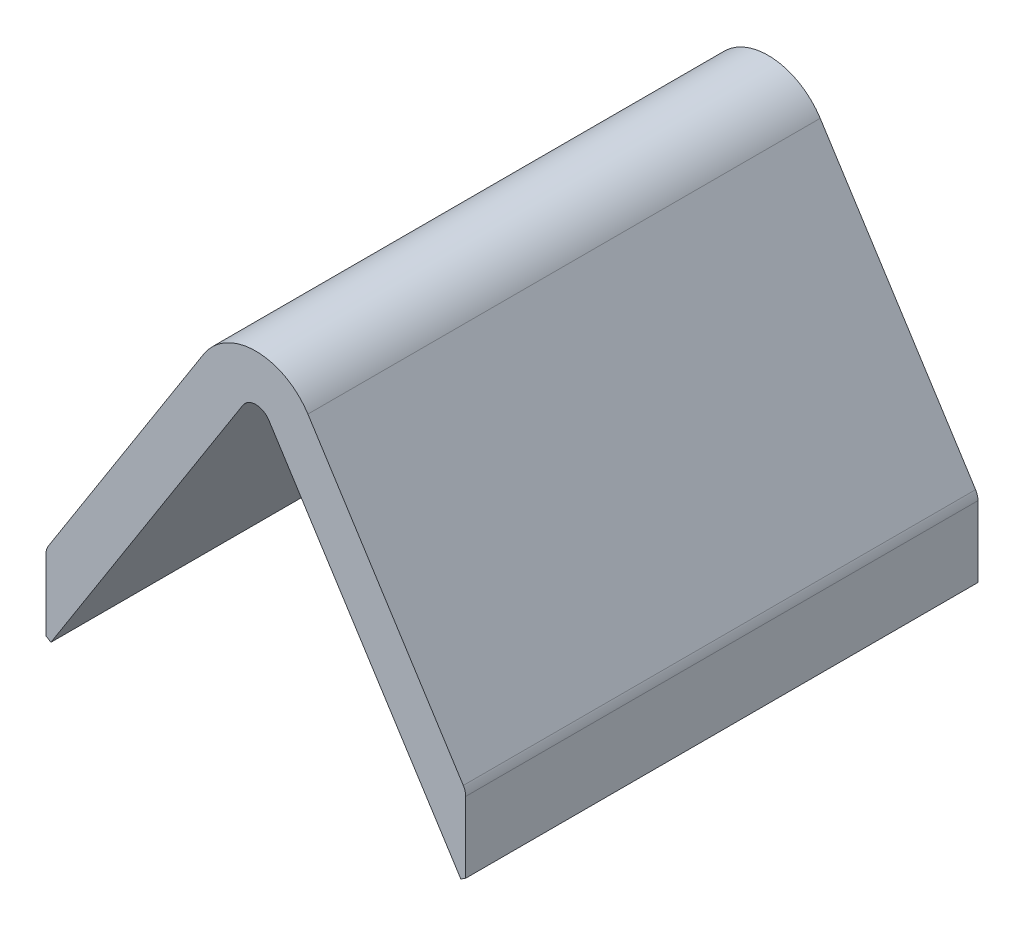
SolidWorks part; units mm, degrees
material "Custom Plastic"
ref_plane "Front Plane" through (0, 0, 0) normal (0, 0, 1) x (1, 0, 0)
ref_plane "Top Plane" through (0, 0, 0) normal (0, 1, 0) x (1, 0, 0)
ref_plane "Right Plane" through (0, 0, 0) normal (1, 0, 0) x (0, 0, -1)
sketch "Sketch1" plane through (0, 0, 0) normal (0, 0, 1) x (1, 0, 0)
  line L0 (0, 0) -> (0, 145.7232) construction
  line L1 (-70.5, -139) -> (70.5, -139) construction
  line L2 (-70.5, -139) -> (-70.5, 139) construction
  line L3 (-70.5, 139) -> (70.5, 139) construction
  line L4 (70.5, -139) -> (70.5, 139) construction
  line L5 (-70.5, -139) -> (70.5, 139) construction
  line L6 (-70.5, 139) -> (70.5, -139) construction
  line L7 (0, 145.7232) -> (-68, 38.9846) construction
  line L8 (-65.5, 9.4079) -> (-1.6868, 109.5746)
  line L9 (-68.0302, 11.0198) -> (-4.217, 111.1865)
  line L10 (-65.5, 9.4079) -> (-68.0302, 11.0198)
  line L11 (-65.5, 9.4079) -> (-65.5, 8.4079)
  line L12 (-65.5, 8.4079) -> (-70.5, 8.4079)
  line L13 (-70.5, 8.4079) -> (-70.5, 37.3253)
  line L14 (-67.217, 40.2137) -> (-16.8678, 119.246)
  line L15 (-68, 14.5577) -> (-68, 37.5272)
  line L16 (-18.5546, 120.3206) -> (-69.717, 40.0118)
  line L17 (65.5, 9.4079) -> (65.5, 8.4079)
  line L18 (65.5, 9.4079) -> (68.0302, 11.0198)
  line L19 (65.5, 8.4079) -> (70.5, 8.4079)
  line L20 (70.5, 8.4079) -> (70.5, 37.3253)
  line L21 (68, 14.5577) -> (68, 37.5272)
  line L22 (65.5, 9.4079) -> (1.6868, 109.5746)
  line L23 (68.0302, 11.0198) -> (4.217, 111.1865)
  line L24 (67.217, 40.2137) -> (16.8678, 119.246)
  line L25 (18.5546, 120.3206) -> (69.717, 40.0118)
  line L26 (-68.0302, 11.0198) -> (-66.4183, 13.55)
  line L27 (-66.4183, 13.55) -> (-68, 14.5577)
  line L28 (66.4183, 13.55) -> (68, 14.5577)
  line L29 (-65.5, 8.4079) -> (-65.5, 3.4079)
  line L30 (-65.5, 3.4079) -> (-15.1236, -135)
  line L31 (-15.1236, -135) -> (15.1236, -135)
  line L32 (25.5253, -74.8874) -> (65.5, 3.4079)
  line L33 (17.9245, -139) -> (-17.9245, -139)
  line L34 (-17.9245, -139) -> (-70.5, 5.4501)
  line L35 (-70.5, 5.4501) -> (-70.5, 8.4079)
  line L36 (-70.5, 8.4079) -> (-70.5, 5.4501)
  line L37 (65.5, 3.4079) -> (15.1236, -135)
  line L38 (17.9245, -139) -> (70.5, 5.4501)
  line L39 (65.5, 8.4079) -> (70.5, 8.4079)
  line L40 (65.5, 8.4079) -> (65.5, 3.4079)
  line L41 (70.5, 5.4501) -> (70.5, 8.4079)
  line L42 (-25.5253, -74.8874) -> (-65.5, 3.4079)
  arc A0 (-1.6868, 109.5746) -> (1.6868, 109.5746) centre (0, 108.5) cw
  arc A1 (-4.217, 111.1865) -> (4.217, 111.1865) centre (0, 108.5) cw
  arc A2 (-16.8678, 119.246) -> (16.8678, 119.246) centre (0, 108.5) cw
  arc A3 (-69.717, 40.0118) -> (-70.5, 37.3253) centre (-65.5, 37.3253) ccw
  arc A4 (-67.217, 40.2137) -> (-68, 37.5272) centre (-63, 37.5272) ccw
  arc A5 (-18.5546, 120.3206) -> (18.5546, 120.3206) centre (0, 108.5) cw
  arc A6 (67.217, 40.2137) -> (68, 37.5272) centre (63, 37.5272) cw
  arc A7 (69.717, 40.0118) -> (70.5, 37.3253) centre (65.5, 37.3253) cw
  arc A9 (-25.5253, -74.8874) -> (25.5253, -74.8874) centre (0, -61.8551) ccw
  circle A10 centre (-1.6868, -115) radius 11
  point P0 (0, 0)
  point P24 (-70.5, 38.7827)
  dimension "D5" = 2
  dimension "D10" = 5
  dimension "D21" = 22
  dimension "D1" = 141
  dimension "D2" = 278
  dimension "D3" = 32.5
  dimension "D4" = 3
  dimension "D6" = 15
  dimension "D7" = 1
  dimension "D8" = 5
  dimension "D9" = 2
  dimension "D11" = 30.5
  dimension "D12" = 100.1667
  dimension "D13" = 148.4079
  dimension "D14" = 3
  dimension "D15" = 2.5
  dimension "D16" = 5
  dimension "D17" = 4
  dimension "D18" = 4
  dimension "D19" = 70
  dimension "D20" = 20
extrude "Boss-Extrude1" add sketch "Sketch1" along normal blind 166 contours A6 L24 A2 L14 A4 L15 L27 L9 A1 L23 L28 L21
